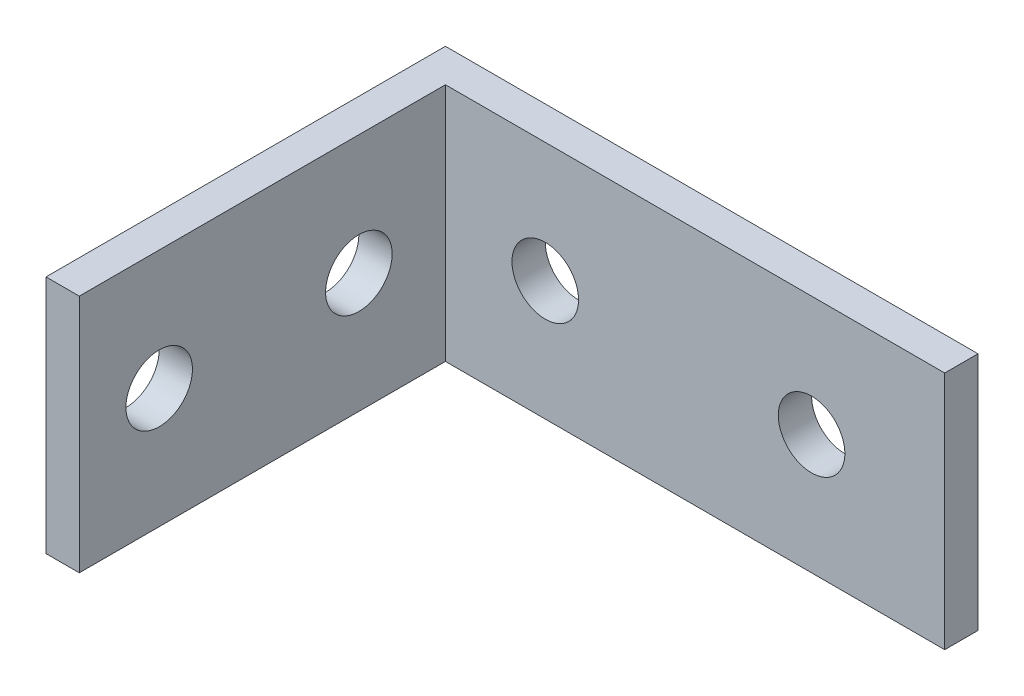
SolidWorks part; units mm, degrees
material "6061-T6 (SS)"
ref_plane "Front Plane" through (0, 0, 0) normal (0, 0, 1) x (1, 0, 0)
ref_plane "Top Plane" through (0, 0, 0) normal (0, 1, 0) x (1, 0, 0)
ref_plane "Right Plane" through (0, 0, 0) normal (1, 0, 0) x (0, 0, -1)
sketch "Sketch1" plane through (0, 0, 0) normal (0, 1, 0) x (1, 0, 0)
  line L0 (0, 0) -> (0, 38.1)
  line L1 (0, 38.1) -> (50.8, 38.1)
  line L2 (0, 0) -> (3.175, 0)
  line L3 (3.175, 0) -> (3.175, 34.925)
  line L4 (3.175, 34.925) -> (50.8, 34.925)
  line L5 (50.8, 34.925) -> (50.8, 38.1)
  dimension "D1" = 3.175
  dimension "D2" = 3.175
  dimension "D3" = 38.1
  dimension "D4" = 50.8
extrude "Boss-Extrude1" add sketch "Sketch1" along normal blind 22.86
hole_wizard "1/4 (0.25) Diameter Hole1" positions "Sketch3" profile "Sketch2" hole size "1/4" standard "ANSI Inch" end condition up to next
sketch "Sketch3" plane through (3.175, 0, 0) normal (1, 0, 0) x (0, 0, -1)
  line L0 (0, 22.86) -> (34.925, 22.86) construction
  line L2 (38.1, 22.86) -> (38.1, 0) construction
  point P0 (7.62, 11.43)
  point P2 (26.67, 11.43)
  dimension "D1" = 11.43
  dimension "D2" = 19.05
  dimension "D3" = 11.43
sketch "Sketch2" plane through (3.175, 11.43, -7.62) normal (0, 1, 0) x (0, 0, -1)
  line L0 (0, 0) -> (0, 3.175)
  line L1 (0, 3.175) -> (3.175, 3.175)
  line L2 (3.175, 3.175) -> (3.175, 0)
  line L5 (3.175, 0) -> (0, 0)
  line L11 (0, -6.35) -> (0, 107.95) construction
  dimension "Thru Hole Dia." = 6.35
  dimension "Thru Hole Depth" = 3.175
hole_wizard "1/4 (0.25) Diameter Hole2" positions "Sketch7" profile "Sketch6" hole size "1/4" standard "ANSI Inch" end condition up to next
sketch "Sketch7" plane through (0, 0, -38.1) normal (0, 0, -1) x (-1, 0, 0)
  line L0 (-50.8, 22.86) -> (-50.8, 0) construction
  line L1 (-50.8, 22.86) -> (0, 22.86) construction
  point P0 (-38.1, 11.43)
  point P2 (-12.7, 11.43)
  dimension "D1" = 25.4
  dimension "D2" = 12.7
  dimension "D3" = 11.43
sketch "Sketch6" plane through (38.1, 11.43, -38.1) normal (1, 0, 0) x (0, 1, 0)
  line L0 (0, 0) -> (0, 3.175)
  line L1 (0, 3.175) -> (3.175, 3.175)
  line L2 (3.175, 3.175) -> (3.175, 0)
  line L5 (3.175, 0) -> (0, 0)
  line L11 (0, -6.35) -> (0, 107.95) construction
  dimension "Thru Hole Dia." = 6.35
  dimension "Thru Hole Depth" = 3.175
